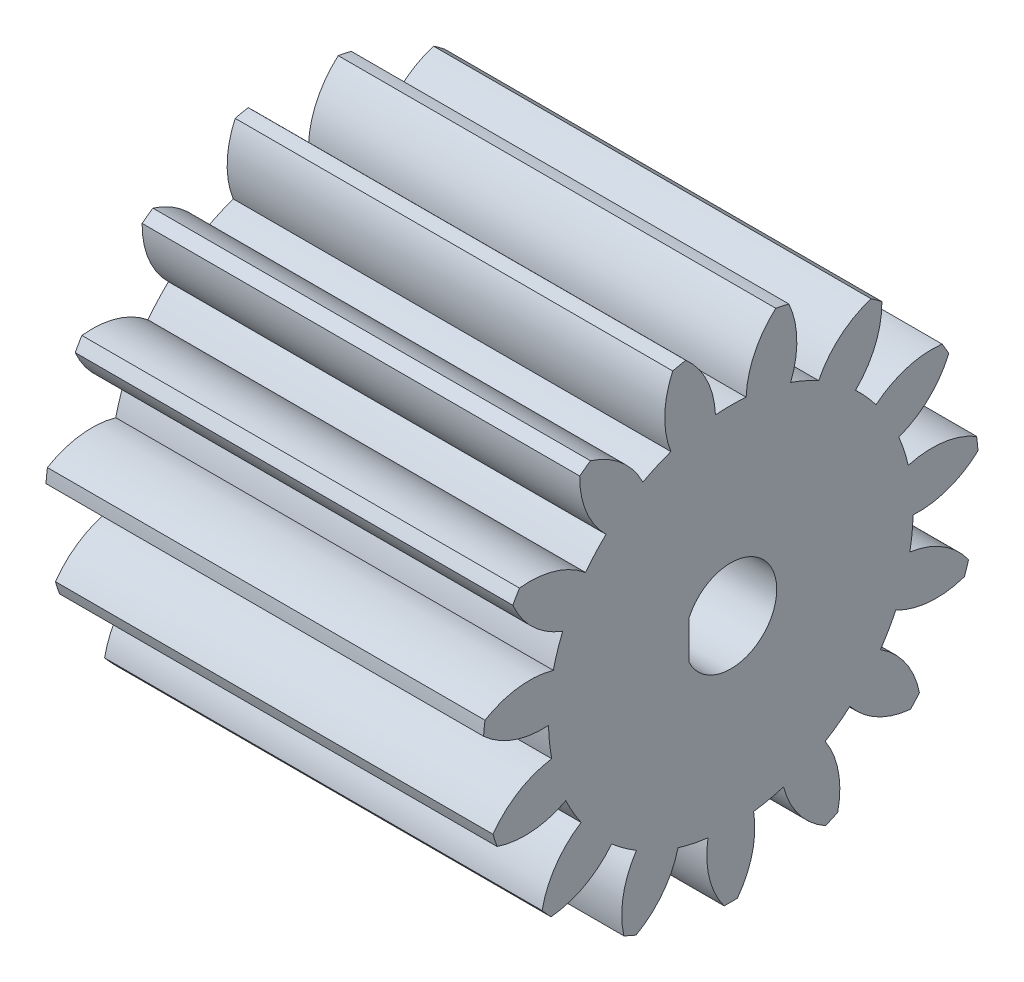
SolidWorks part; units mm, degrees
ref_plane "Plane1" through (0, 0, 0) normal (0, 0, 1) x (1, 0, 0)
ref_plane "Plane2" through (0, 0, 0) normal (0, 1, 0) x (1, 0, 0)
ref_plane "Plane3" through (0, 0, 0) normal (1, 0, 0) x (0, 0, -1)
sketch "HoldingSke" plane through (0, 0, 0) normal (0, 1, 0) x (1, 0, 0)
  line L0 (0, 0) -> (0.483, -0.1294)
  line L1 (-15, 0) -> (100, 0) construction
  line L2 (0, 0) -> (-2.1039, 2.3779)
  line L3 (0, 0) -> (-11.863, 4.5341)
  line L4 (0, 0) -> (8.3417, 2.2352)
  line L5 (0, 0) -> (-46.8476, -17.4728)
  line L6 (0, 0) -> (-24.8689, -16.7791)
  line L7 (-2.1039, 2.3779) -> (8.6586, 51.2059)
  line L8 (-76.2, 54.61) -> (-74.4, 54.61)
  line L9 (-71.009, 38.7566) -> (-53.1078, 45.2721)
  line L10 (-76.2, 71.12) -> (104.1128, 71.12)
  line L11 (0, 0) -> (-30, 0)
  line L12 (-76.2, 101.6) -> (-76.133, 101.6)
  line L13 (24.9733, 27.94) -> (52.9518, 28.4284)
  line L14 (24.9733, 27.94) -> (24.9743, 27.94)
  line L15 (24.9733, 27.94) -> (100.4006, 29.5858)
  line L16 (-63.627, -2) -> (-12.827, -2)
  circle A0 centre (0, 0) radius 5
  circle A1 centre (0, 0) radius 12.499
  circle A2 centre (0, 0) radius 37.5
  circle A3 centre (0, 0) radius 5
  dimension "MHD" = 24.998
  dimension "Hub_dia" = 75
  dimension "Bore" = 10
  dimension "MBD" = 10
  dimension "Num_teeth" = 15
  dimension "Pitch" = 0.5
  dimension "Overall_len" = 50
  dimension "Show_teeth" = 15
  dimension "Thickness" = 30
  dimension "OAL" = 50.0001
  dimension "T_dim" = 1.8
  dimension "Ap" = 20
  dimension "H" = 19.05
  dimension "Pitch_radius" = 180.3128
  dimension "Width" = 30
  dimension "Backlash" = 0.067
  dimension "Addendum_fac" = 1
  dimension "Dedendum_fac" = 1.25
  dimension "Clearance_fac" = 0.25
  dimension "Dedendum_add" = 0.001
  dimension "Module" = 2
sketch "BasProSke" plane through (0, 0, 0) normal (0, 1, 0) x (1, 0, 0)
  line L0 (-10, 0) -> (60, 0) construction
  line L1 (0, 0) -> (0, 17)
  line L2 (0, 0) -> (30, 0)
  line L3 (30, 0) -> (30, 17)
  line L4 (30, 17) -> (0, 17)
  dimension "Thickness" = 30
  dimension "Diameter" = 34
revolve "Base-Revolve" add sketch "BasProSke" angle 360 about L0
sketch "TooCutSke" plane through (0, 0, 0) normal (1, 0, 0) x (0, 0, -1)
  line L1 (0, 0) -> (0, 107) construction
  line L2 (0, 0) -> (-1.6851, 14.905) construction
  line L3 (0, 0) -> (-6.2081, 29.2069) construction
  line L4 (-1.6851, 14.905) -> (-3.1041, 14.6034) construction
  arc A0 (1.0501, 12.4548) -> (-1.0501, 12.4548) centre (0, 0) ccw
  arc A1 (3.1109, 16.7388) -> (-3.1109, 16.7388) centre (0, 0) ccw
  circle A2 centre (0, 0) radius 15 construction
  circle A3 centre (0, 0) radius 14.0954 construction
  arc A4 (-1.0501, 12.4548) -> (-3.1109, 16.7388) centre (-7.045, 12.2085) ccw
  arc A5 (3.1109, 16.7388) -> (1.0501, 12.4548) centre (7.045, 12.2085) ccw
  dimension "Root_dia" = 24.998
  dimension "Overcut_dia" = 34.0508
  dimension "Pitch_dia" = 30
  dimension "Base_dia" = 28.1908
  dimension "Flank_rad" = 6
  dimension "Half_ang" = 12
  dimension "Half_CT" = 1.4507
extrude "ToothCut" cut sketch "TooCutSke" along normal through all
fillet "Breaks" [suppressed] radius 0.04
fillet "RootFillets" [suppressed] radius 0.501
pattern_circular "TeethCuts" count 15 every 24 about axis through (-10, 0, 0) along (1, 0, 0) of "ToothCut", "RootFillets", "Breaks"
sketch "HubNeaOneSke" plane through (0, 0, 0) normal (-1, 0, 0) x (0, 0, 1)
  circle A0 centre (0, 0) radius 12.499
  dimension "Diameter" = 24.998
extrude "HubNearOne" [suppressed] add sketch "HubNeaOneSke" along normal blind 20.0001
sketch "HubNeaBotSke" plane through (0, 0, 0) normal (-1, 0, 0) x (0, 0, 1)
  circle A0 centre (0, 0) radius 12.499
  dimension "Diameter" = 24.998
extrude "HubNearBoth" [suppressed] add sketch "HubNeaBotSke" along normal blind 10
ref_plane "FarPln" through (30, 0, 0) normal (1, 0, 0) x (0, 0, -1)
sketch "HubFarSke" plane through (30, 0, 0) normal (1, 0, 0) x (0, 0, -1)
  circle A0 centre (0, 0) radius 12.499
  dimension "Diameter" = 24.998
extrude "HubFar" [suppressed] add sketch "HubFarSke" along normal blind 10
sketch "BorSke" plane through (0, 0, 0) normal (1, 0, 0) x (0, 0, -1)
  circle A0 centre (0, 0) radius 5
  dimension "Diameter" = 10
extrude "Bore" cut sketch "BorSke" along normal mid plane 100.0001
sketch "KeySke" plane through (0, 0, 0) normal (1, 0, 0) x (0, 0, -1)
  line L0 (-2, 0) -> (-2, 6.8)
  line L1 (-2, 6.8) -> (2, 6.8)
  line L2 (2, 6.8) -> (2, 0)
  line L3 (0, 0) -> (0, 34) construction
  line L4 (-2, 0) -> (2, 0)
  dimension "Offset" = 6.8
  dimension "Width" = 4
extrude "Keyway" [suppressed] cut sketch "KeySke" along normal mid plane 100.0001
pattern_circular "Keyway2" [suppressed] count 2 every 90 about axis through (-10, 0, 0) along (1, 0, 0)
sketch "Esboço1" plane through (30, 0, 0) normal (1, 0, 0) x (0, 0, -1)
  circle A0 centre (0, 0) radius 5
extrude "Ressalto-extrusão1" add sketch "Esboço1" against normal blind 30
sketch "Esboço2" plane through (30, 0, 0) normal (1, 0, 0) x (0, 0, -1)
  line L2 (-2.85, 1.3416) -> (-2.85, -1.3416)
  arc A0 (-2.85, -1.3416) -> (-2.85, 1.3416) centre (0, 0) ccw
  dimension "D1" = 6.3
  dimension "D2" = 6
extrude "Corte-extrusão1" cut sketch "Esboço2" against normal up to next
equation "' \"Module@HoldingSke\" = 6.35"
equation "' \"Num_teeth@HoldingSke\" = 12"
equation "' \"Ap@HoldingSke\" =  20"
equation "' \"Ap@HoldingSke\" = 20"
equation "' \"Width@HoldingSke\" = 0.5 * 25.4"
equation "' \"Hub_dia@HoldingSke\"= 1 * 25.4"
equation "' \"Hub_dia@HoldingSke\" = 1 * 25.4"
equation "' \"Overall_len@HoldingSke\" = 1.0 * 25.4"
equation "' \"Bore@HoldingSke\" = 0.75 * 25.4"
equation "' \"T_dim@HoldingSke\" = 0.1 * 25.4"
equation "' \"Width@KeySke\" = 0.25 * 25.4"
equation "' \"Show_teeth@HoldingSke\" = 13"
equation "' \"Backlash@HoldingSke\" = 0.009 * 25.4"
equation "' \"Addendum_fac@HoldingSke\" = 1.0"
equation "' \"Dedendum_fac@HoldingSke\" = 1.25"
equation "' \"Dedendum_add@HoldingSke\" = 0.00005 * 25.4"
equation "' \"Clearance_fac@HoldingSke\" = 0.25"
equation "\"Pitch@HoldingSke\" = 1 / \"Module@HoldingSke\""
equation "\"Overcut_dia@TooCutSke\" = (\"Num_teeth@HoldingSke\" + 2 * \"Addendum_fac@HoldingSke\") / \"Pitch@HoldingSke\" + 0.002 * 25.4"
equation "\"Pitch_dia@TooCutSke\" = \"Num_teeth@HoldingSke\" / \"Pitch@HoldingSke\""
equation "\"Base_dia@TooCutSke\" = \"Num_teeth@HoldingSke\" / \"Pitch@HoldingSke\" * cos((\"Ap@HoldingSke\"  * 3.14159265 / 180))"
equation "\"Root_dia@TooCutSke\" = (\"Num_teeth@HoldingSke\" + 2) / \"Pitch@HoldingSke\" - 2 * (\"Addendum_fac@HoldingSke\" + \"Dedendum_fac@HoldingSke\") / \"Pitch@HoldingSke\" - \"Dedendum_add@HoldingSke\" * 2"
equation "\"Half_ang@TooCutSke\" = 180 / \"Num_teeth@HoldingSke\""
equation "\"Half_CT@TooCutSke\" = \"Num_teeth@HoldingSke\" / \"Pitch@HoldingSke\" * sin((3.14159265 / 2 / \"Num_teeth@HoldingSke\")) / 2 - 7 * \"Backlash@HoldingSke\" / 4"
equation "\"Flank_rad@TooCutSke\" = \"Num_teeth@HoldingSke\" / \"Pitch@HoldingSke\" / 5"
equation "\"Radius@RootFillets\" = \"Clearance_fac@HoldingSke\" / \"Pitch@HoldingSke\" + \"Dedendum_add@HoldingSke\""
equation "\"Break_rad@Breaks\" = 0.02 / \"Pitch@HoldingSke\""
equation "\"Thickness@HoldingSke\" = \"Width@HoldingSke\""
equation "\"OAL@HoldingSke\" = \"Thickness@HoldingSke\""
equation "\"MHD@HoldingSke\" = (\"Num_teeth@HoldingSke\" + 2) / \"Pitch@HoldingSke\" - 2 * (\"Addendum_fac@HoldingSke\" + \"Dedendum_fac@HoldingSke\")  / \"Pitch@HoldingSke\" - \"Dedendum_add@HoldingSke\" * 2"
equation "\"MBD@HoldingSke\" = (\"Num_teeth@HoldingSke\" + 2) / \"Pitch@HoldingSke\" - 2 * (\"Addendum_fac@HoldingSke\" + \"Dedendum_fac@HoldingSke\")  / \"Pitch@HoldingSke\" - \"Dedendum_add@HoldingSke\" * 2 - 0.002 * 25.4"
equation "\"MHD@HoldingSke\" = ((sgn( \"MHD@HoldingSke\" - \"Hub_dia@HoldingSke\" )-1)*( \"MHD@HoldingSke\" - \"Hub_dia@HoldingSke\" ))/-2+ \"Hub_dia@HoldingSke\""
equation "\"MBD@HoldingSke\" = ((sgn( \"MBD@HoldingSke\" - \"Bore@HoldingSke\" )-1)*( \"MBD@HoldingSke\" - \"Bore@HoldingSke\" ))/-2+ \"Bore@HoldingSke\""
equation "\"OAL@HoldingSke\" = ((sgn( \"OAL@HoldingSke\" - \"Overall_len@HoldingSke\" )+1)*( \"OAL@HoldingSke\" - \"Overall_len@HoldingSke\" ))/2 + \"Overall_len@HoldingSke\" + 0.000002 * 25.4"
equation "\"Num_teeth@TeethCuts\" = int( \"Show_teeth@HoldingSke\" ) + 1"
equation "\"Num_teeth@TeethCuts\" = ((sgn( \"Num_teeth@TeethCuts\" - \"Num_teeth@HoldingSke\" )-1)*( \"Num_teeth@TeethCuts\" - \"Num_teeth@HoldingSke\" ))/-2+ \"Num_teeth@HoldingSke\""
equation "\"Num_teeth@TeethCuts\" = ((sgn( \"Num_teeth@TeethCuts\" - 2.0)+1)*( \"Num_teeth@TeethCuts\" - 2.0))/2 +2.0"
equation "\"Angle@TeethCuts\" = 360.0 / \"Num_teeth@HoldingSke\""
equation "\"Diameter@BasProSke\" = (\"Num_teeth@HoldingSke\" + 2 * \"Addendum_fac@HoldingSke\") / \"Pitch@HoldingSke\""
equation "\"Thickness@BasProSke\"  = \"Thickness@HoldingSke\""
equation "' \"Fillet_rad@BasProSke\" =  \"Thickness@HoldingSke\" * 0.05"
equation "' \"Fillet_rad@BasProSke\" = \"Thickness@HoldingSke\" * 0.05"
equation "\"MHD@HoldingSke\" = ((sgn( \"MHD@HoldingSke\" - \"Root_dia@TooCutSke\" )-1)*( \"MHD@HoldingSke\" - \"Root_dia@TooCutSke\" ))/-2+ \"Root_dia@TooCutSke\""
equation "\"Diameter@HubNeaOneSke\" = \"MHD@HoldingSke\""
equation "\"Length@HubNearOne\" = \"OAL@HoldingSke\" - \"Thickness@BasProSke\""
equation "\"Diameter@HubNeaBotSke\" = \"MHD@HoldingSke\""
equation "\"Length@HubNearBoth\" = ( \"OAL@HoldingSke\" - \"Thickness@BasProSke\" ) / 2.0"
equation "\"Thickness@FarPln\" = \"Thickness@BasProSke\""
equation "\"Diameter@HubFarSke\" = \"MHD@HoldingSke\""
equation "\"Length@HubFar\" = ( \"OAL@HoldingSke\" - \"Thickness@BasProSke\" ) / 2.0"
equation "\"Diameter@BorSke\" = \"MBD@HoldingSke\""
equation "\"D1@Bore\" = \"OAL@HoldingSke\" * 2.0"
equation "\"D1@Keyway\" = \"OAL@HoldingSke\" * 2.0"
equation "\"Offset@KeySke\" = \"T_dim@HoldingSke\" + \"MBD@HoldingSke\" / 2.0"
